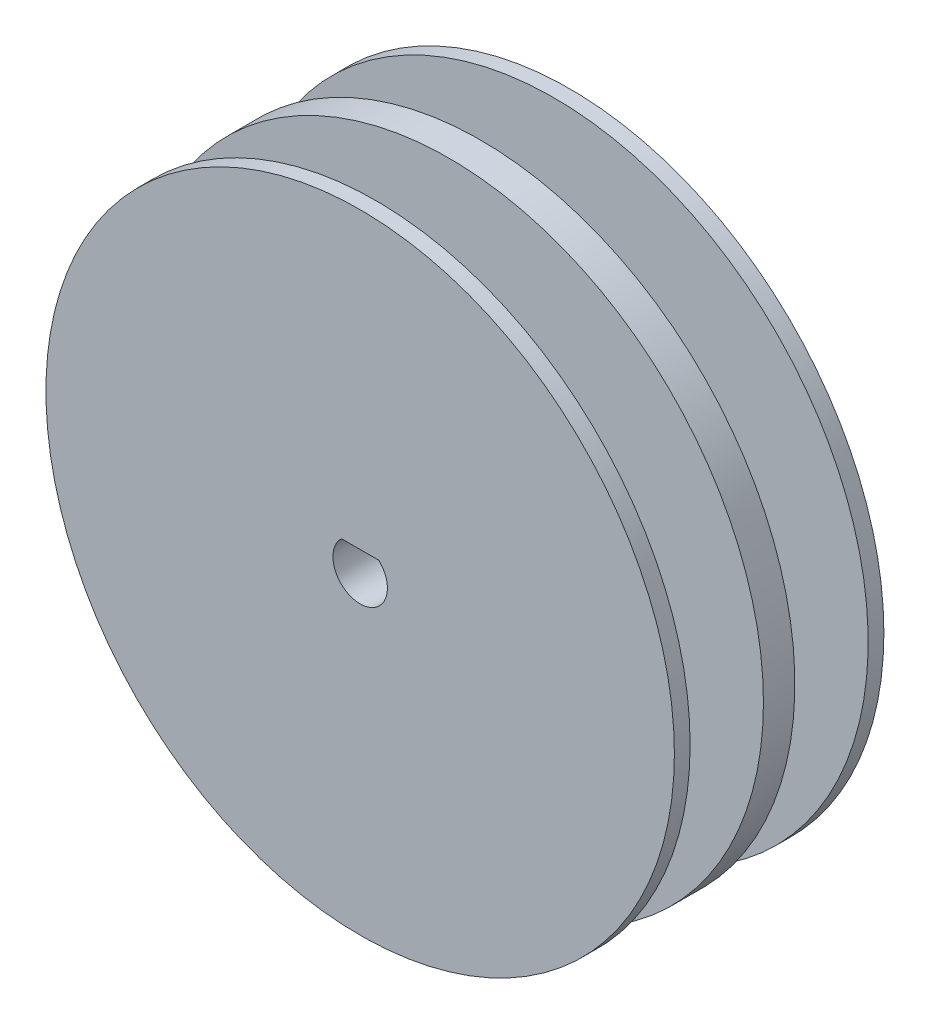
SolidWorks part; units mm, degrees
material "Custom Plastic"
ref_plane "Front Plane" through (0, 0, 0) normal (0, 0, 1) x (1, 0, 0)
ref_plane "Top Plane" through (0, 0, 0) normal (0, 1, 0) x (1, 0, 0)
ref_plane "Right Plane" through (0, 0, 0) normal (1, 0, 0) x (0, 0, -1)
sketch "Sketch1" plane through (0, 0, 0) normal (0, 0, 1) x (1, 0, 0)
  circle A0 centre (0, 0) radius 30
  circle A1 centre (0, 0) radius 20
  dimension "D1" = 60
  dimension "D2" = 40
extrude "Boss-Extrude1" add sketch "Sketch1" along normal mid plane 20 contours A1 | A0 A1
ref_plane "Plane1" through (0, 0, 5) normal (0, 0, 1) x (1, 0, 0)
sketch "Sketch2" plane through (0, 0, 5) normal (0, 0, 1) x (1, 0, 0)
  circle A0 centre (0, 0) radius 20
  dimension "D1" = 40
extrude "Cut-Extrude1" cut sketch "Sketch2" against normal mid plane 7 flip side to cut
mirror "Mirror1" about plane through (0, 0, 0) normal (0, 0, 1) of "Cut-Extrude1"
sketch "Sketch3" plane through (0, 0, 0) normal (1, 0, 0) x (0, 0, -1)
  line L0 (0, 0) -> (0, 10) construction
  line L2 (10, -30) -> (10, 30) construction
  line L3 (10, 0) -> (10, 20) construction
  line L4 (8.5, 20) -> (1.5, 20) construction
  line L5 (0, 10) -> (10, 10) construction
  line L6 (0, 10) -> (-10, 10) construction
  line L7 (-10, 30) -> (-10, -30) construction
  circle A0 centre (-5, 10) radius 1.6
  circle A1 centre (5, 10) radius 1.6
  point P12 (10, 10)
  dimension "D1" = 3.2
extrude "Cut-Extrude2" cut sketch "Sketch3" against normal through all both and the other way through all
sketch "Sketch4" plane through (0, 0, -10) normal (0, 0, -1) x (-1, 0, 0)
  line L0 (-1.7748, 1.9) -> (1.7748, 1.9)
  line L1 (0, 0) -> (0, -2.6) construction
  arc A0 (-1.7748, 1.9) -> (1.7748, 1.9) centre (0, 0) ccw
  dimension "D1" = 5.2
  dimension "D2" = 4.5
extrude "Cut-Extrude3" cut sketch "Sketch4" against normal through all both
